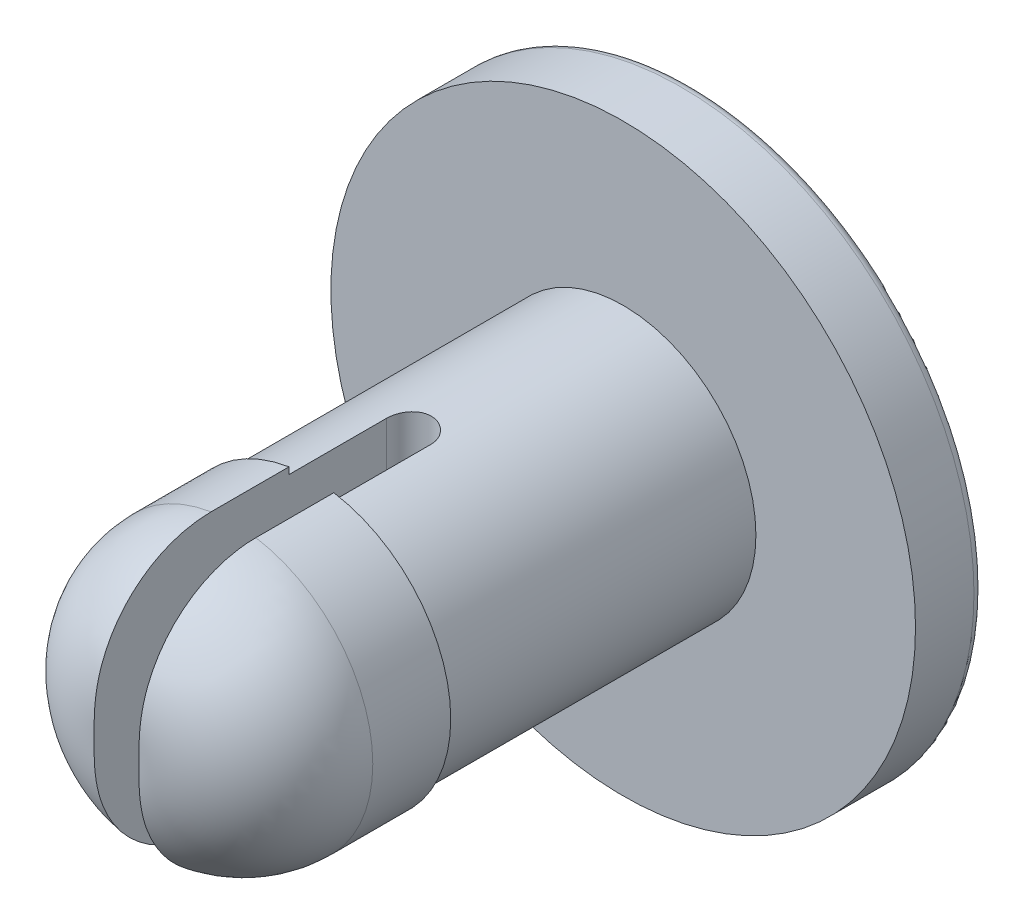
SolidWorks part; units mm, degrees
ref_plane "Front Plane" through (0, 0, 0) normal (0, 0, 1) x (1, 0, 0)
ref_plane "Top Plane" through (0, 0, 0) normal (0, 1, 0) x (1, 0, 0)
ref_plane "Right Plane" through (0, 0, 0) normal (1, 0, 0) x (0, 0, -1)
sketch "Sketch2" plane through (0, 0, 0) normal (0, 0, 1) x (1, 0, 0)
  circle A0 centre (0, 0) radius 7.5
  dimension "D1" = 15
extrude "Boss-Extrude1" add sketch "Sketch2" along normal blind 1.75
fillet "Fillet1" radius 0.25 1 edges at (7.5, 0, 0)
sketch "Sketch3" plane through (0, 0, 1.75) normal (0, 0, 1) x (1, 0, 0)
  circle A0 centre (0, 0) radius 3.405
  dimension "D1" = 6.81
extrude "Boss-Extrude2" add sketch "Sketch3" along normal blind 8
sketch "Sketch4" plane through (0, 0, 9.75) normal (0, 0, 1) x (1, 0, 0)
  circle A0 centre (0, 0) radius 3.575
  dimension "D1" = 7.15
extrude "Boss-Extrude3" add sketch "Sketch4" along normal blind 5
fillet "Fillet3" radius 3 1 edges at (3.575, 0, 14.75)
sketch "Sketch5" plane through (0, 0, 0) normal (0, 1, 0) x (1, 0, 0)
  line L1 (0.575, -14.75) -> (0.575, -7.25)
  line L5 (-0.575, -7.25) -> (-0.575, -14.75)
  line L6 (-0.575, -14.75) -> (0.575, -14.75)
  arc A0 (-0.575, -7.25) -> (0.575, -7.25) centre (0, -7.25) cw
  dimension "D1" = 7.5
extrude "Cut-Extrude1" cut sketch "Sketch5" against normal through all both and the other way through all
